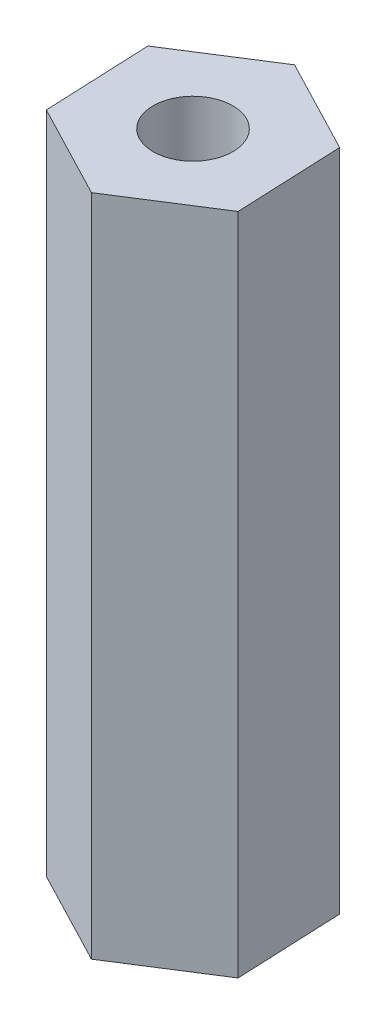
SolidWorks part; units mm, degrees
material "Brass"
ref_plane "Front Plane" through (0, 0, 0) normal (0, 0, 1) x (1, 0, 0)
ref_plane "Top Plane" through (0, 0, 0) normal (0, 1, 0) x (1, 0, 0)
ref_plane "Right Plane" through (0, 0, 0) normal (1, 0, 0) x (0, 0, -1)
sketch "Sketch1" plane through (0, 0, 0) normal (0, 1, 0) x (1, 0, 0)
  line L1 (-3.547, 1.849) -> (-3.3748, -2.1473)
  line L2 (-3.3748, -2.1473) -> (0.1722, -3.9963)
  line L3 (0.1722, -3.9963) -> (3.547, -1.849)
  line L4 (3.547, -1.849) -> (3.3748, 2.1473)
  line L5 (3.3748, 2.1473) -> (-0.1722, 3.9963)
  line L6 (-0.1722, 3.9963) -> (-3.547, 1.849)
  circle A0 centre (0, 0) radius 3.4641 construction
  dimension "D1" = 4
extrude "Boss-Extrude2" add sketch "Sketch1" along normal blind 25
sketch "Sketch3" plane through (0, 25, 0) normal (0, 1, 0) x (1, 0, 0)
  circle A0 centre (0, 0) radius 1.5
  dimension "D1" = 3
extrude "Cut-Extrude1" cut sketch "Sketch3" against normal blind 25
